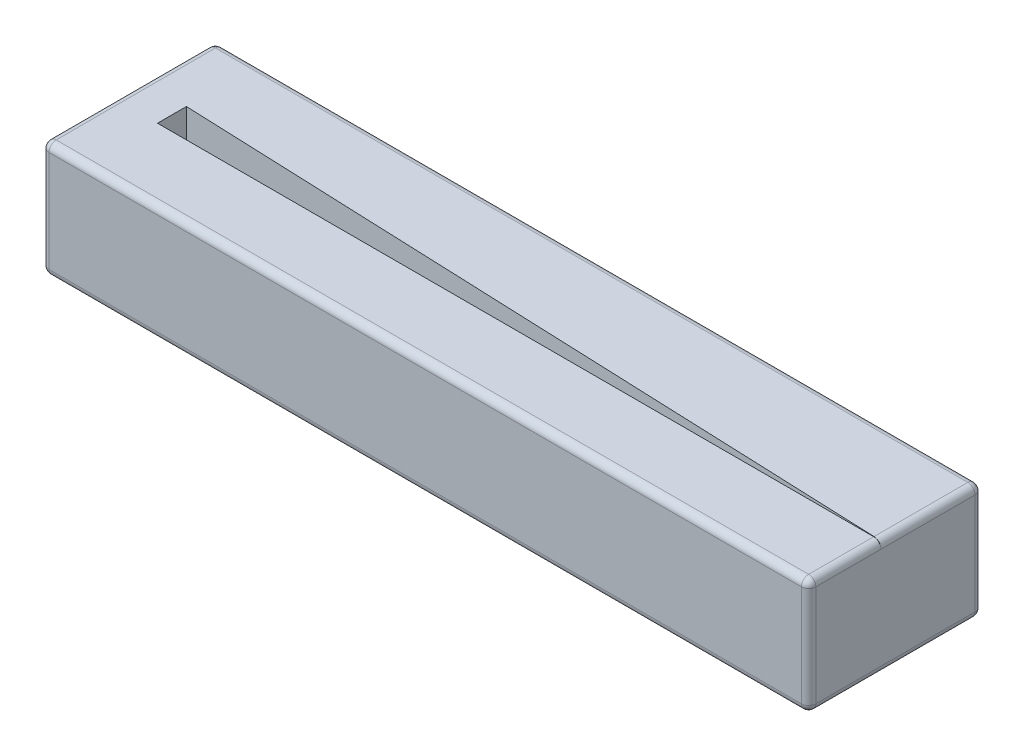
SolidWorks part; units mm, degrees
ref_plane "Front Plane" through (0, 0, 0) normal (0, 0, 1) x (1, 0, 0)
ref_plane "Top Plane" through (0, 0, 0) normal (0, 1, 0) x (1, 0, 0)
ref_plane "Right Plane" through (0, 0, 0) normal (1, 0, 0) x (0, 0, -1)
sketch "Sketch1" plane through (0, 0, 0) normal (0, 1, 0) x (1, 0, 0)
  line L0 (0, 1) -> (50.05, -1)
  line L1 (0, 6) -> (50, 6)
  line L2 (0, 6) -> (0, -6)
  line L3 (0, -6) -> (50, -6)
  line L4 (50, 6) -> (50, -6)
  line L5 (50.05, -1) -> (0, -1)
  line L6 (0, -1) -> (0, 1)
  point P4 (0, 0)
  point P15 (0, 0)
  dimension "D1" = 50
  dimension "D2" = 2
  dimension "D3" = 0.05
  dimension "D4" = 5
extrude "Boss-Extrude1" add sketch "Sketch1" along normal blind 5 contours L4 L5 L2 L3 | L4 L1 L2 L0
sketch "Sketch2" plane through (0, 0, 0) normal (0, -1, 0) x (1, 0, 0)
  line L0 (50, -6) -> (50, 0.998) construction
  line L1 (0, 6) -> (50, 6)
  line L2 (0, 6) -> (0, -6)
  line L3 (0, -6) -> (50, -6)
  line L4 (50, 6) -> (50, -6)
  line L5 (0, -6) -> (50, -6) construction
extrude "Boss-Extrude2" add sketch "Sketch2" along normal blind 3 separate body
sketch "Sketch3" plane through (0, -3, 0) normal (0, -1, 0) x (1, 0, 0)
  line L12 (0, -6) -> (50, -6) construction
  line L13 (0, 6) -> (-3, 6)
  line L14 (0, 6) -> (0, -6)
  line L15 (0, -6) -> (-3, -6)
  line L16 (-3, 6) -> (-3, -6)
  dimension "D1" = 3
extrude "Boss-Extrude3" add sketch "Sketch3" against normal blind 8
fillet "Fillet1" radius 0.5 13 edges at (23.5, -3, -6) (23.5, 5, -6) (-3, 1, -6) (50, 1, -6) (-3, -3, 0) (-3, 5, 0) (50, -3, 0) (-3, 1, 6) (23.5, 5, 6) (50, 1, 6) (23.5, -3, 6) (50, 5, 3.5) (50, 5, -2.501)
